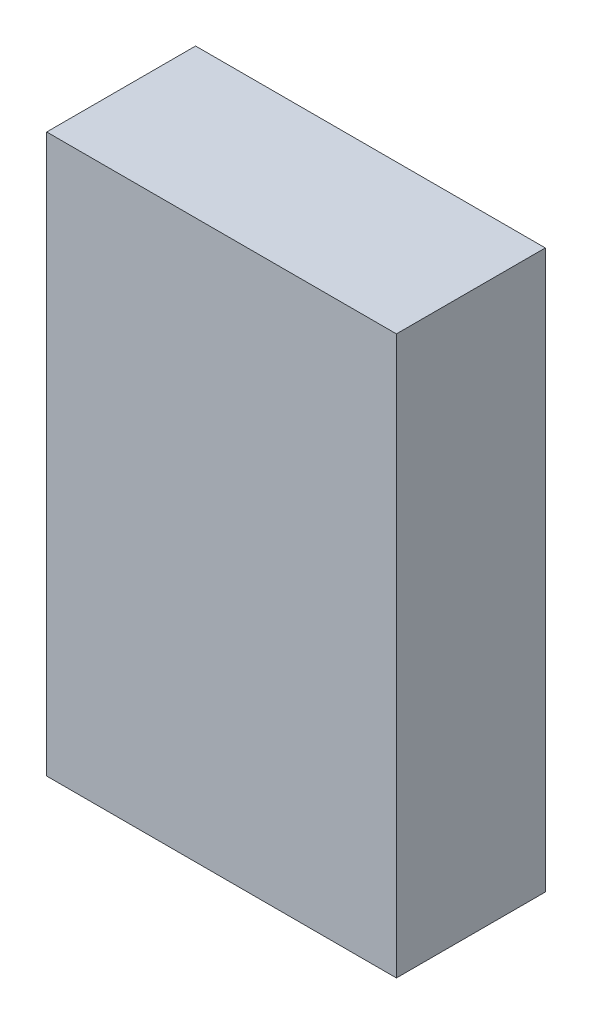
SolidWorks part; units mm, degrees
ref_plane "Front Plane" through (0, 0, 0) normal (0, 0, 1) x (1, 0, 0)
ref_plane "Top Plane" through (0, 0, 0) normal (0, 1, 0) x (1, 0, 0)
ref_plane "Right Plane" through (0, 0, 0) normal (1, 0, 0) x (0, 0, -1)
sketch "Sketch1" plane through (0, 0, 0) normal (0, 0, 1) x (1, 0, 0)
  line L1 (-10.1, -16.11) -> (10.1, -16.11)
  line L2 (-10.1, -16.11) -> (-10.1, 16.11)
  line L3 (-10.1, 16.11) -> (10.1, 16.11)
  line L4 (10.1, -16.11) -> (10.1, 16.11)
  line L5 (-10.1, -16.11) -> (10.1, 16.11) construction
  line L6 (-10.1, 16.11) -> (10.1, -16.11) construction
  point P0 (0, 0)
extrude "Envelope" add sketch "Sketch1" along normal blind 8.6
